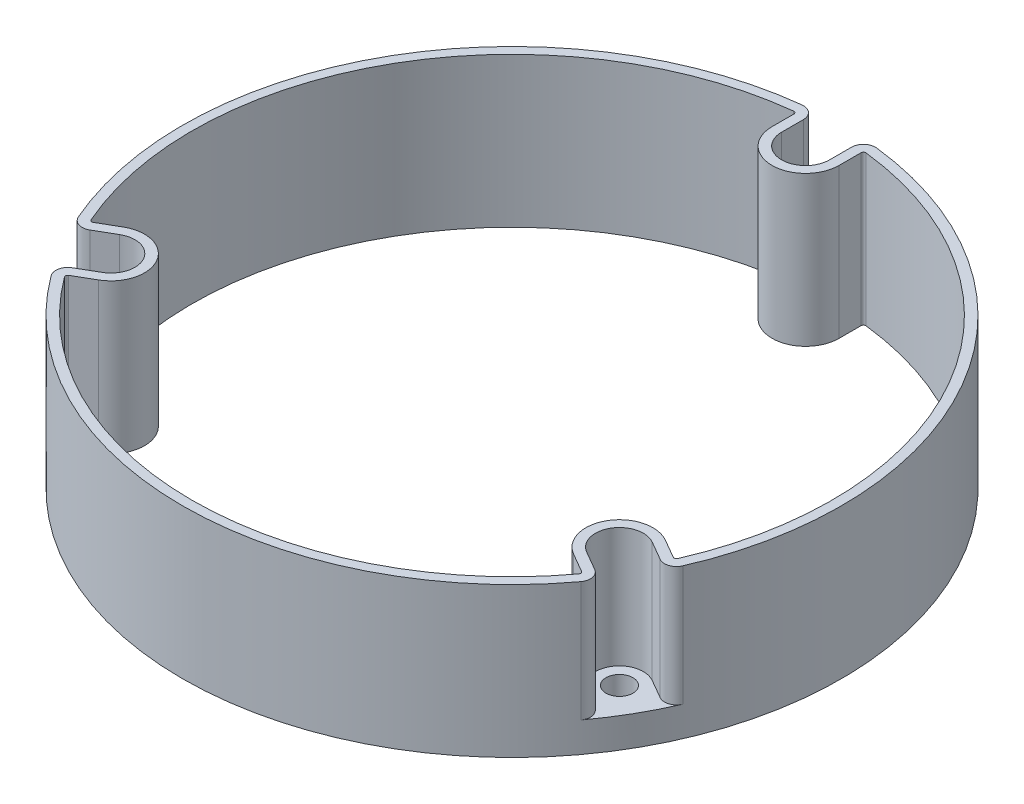
SolidWorks part; units mm, degrees
ref_plane "Front Plane" through (0, 0, 0) normal (0, 0, 1) x (1, 0, 0)
ref_plane "Top Plane" through (0, 0, 0) normal (0, 1, 0) x (1, 0, 0)
ref_plane "Right Plane" through (0, 0, 0) normal (1, 0, 0) x (0, 0, -1)
sketch "Sketch2" plane through (0, 0, 0) normal (0, 1, 0) x (1, 0, 0)
  line L0 (-4, 52.6593) -> (-4, 49)
  line L1 (-4, 49) -> (4, 49) construction
  line L2 (4, 49) -> (4, 52.6593)
  line L3 (0, 49) -> (0, 55) construction
  line L4 (47.6043, -22.8655) -> (44.4352, -21.0359)
  line L5 (40.4352, -27.9641) -> (43.6043, -29.7937)
  line L6 (-43.6043, -29.7937) -> (-40.4352, -27.9641)
  line L7 (-44.4352, -21.0359) -> (-47.6043, -22.8655)
  line L8 (0, 0) -> (0, 49) construction
  line L9 (0, 0) -> (42.4352, -24.5) construction
  arc A0 (-6.2264, 54.6464) -> (-50.4384, -21.931) centre (0, 0) ccw
  arc A1 (-4, 49) -> (4, 49) centre (0, 49) ccw
  arc A2 (-4, 54.8544) -> (4, 54.8544) centre (0, 0) cw construction
  arc A3 (44.4352, -21.0359) -> (40.4352, -27.9641) centre (42.4352, -24.5) ccw
  arc A4 (-40.4352, -27.9641) -> (-44.4352, -21.0359) centre (-42.4352, -24.5) ccw
  arc A5 (50.4384, -21.931) -> (6.2264, 54.6464) centre (0, 0) ccw
  arc A6 (-44.212, -32.7154) -> (44.212, -32.7154) centre (0, 0) ccw
  arc A7 (-44.212, -32.7154) -> (-43.6043, -29.7937) centre (-42.6043, -31.5258) cw
  arc A8 (-47.6043, -22.8655) -> (-50.4384, -21.931) centre (-48.6043, -21.1335) cw
  arc A9 (50.4384, -21.931) -> (47.6043, -22.8655) centre (48.6043, -21.1335) cw
  arc A10 (44.212, -32.7154) -> (43.6043, -29.7937) centre (42.6043, -31.5258) ccw
  arc A11 (6.2264, 54.6464) -> (4, 52.6593) centre (6, 52.6593) ccw
  arc A12 (-4, 52.6593) -> (-6.2264, 54.6464) centre (-6, 52.6593) ccw
  dimension "D1" = 110
  dimension "D2" = 4
  dimension "D6" = 2
  dimension "D3" = 6
  dimension "D5" = 120
  dimension "D4" = 3
extrude "Extrude-Thin1" add sketch "Sketch2" along normal blind 25 thin
sketch "Sketch3" plane through (0, 0, 0) normal (0, -1, 0) x (1, 0, 0)
  line L6 (-43.6043, 29.7937) -> (-40.4352, 27.9641)
  line L7 (-44.4352, 21.0359) -> (-47.6043, 22.8655)
  line L8 (-4, -52.6593) -> (-4, -49)
  line L9 (4, -49) -> (4, -52.6593)
  line L10 (47.6043, 22.8655) -> (44.4352, 21.0359)
  line L11 (40.4352, 27.9641) -> (43.6043, 29.7937)
  line L12 (-43.6043, 29.7937) -> (-40.4352, 27.9641)
  line L13 (-44.4352, 21.0359) -> (-47.6043, 22.8655)
  line L14 (-4, -52.6593) -> (-4, -49)
  line L15 (4, -49) -> (4, -52.6593)
  line L16 (47.6043, 22.8655) -> (44.4352, 21.0359)
  line L17 (40.4352, 27.9641) -> (43.6043, 29.7937)
  arc A0 (-44.212, 32.7154) -> (-50.4384, 21.931) centre (0, 0) ccw
  arc A1 (50.4384, 21.931) -> (44.212, 32.7154) centre (0, 0) ccw
  arc A2 (-6.2264, -54.6464) -> (6.2264, -54.6464) centre (0, 0) ccw
  circle A3 centre (-42.4352, 24.5) radius 2.25
  circle A4 centre (42.4352, 24.5) radius 2.25
  circle A5 centre (0, -49) radius 2.25
  arc A12 (-44.212, 32.7154) -> (-43.6043, 29.7937) centre (-42.6043, 31.5258) ccw
  arc A13 (-44.4352, 21.0359) -> (-40.4352, 27.9641) centre (-42.4352, 24.5) ccw
  arc A14 (-47.6043, 22.8655) -> (-50.4384, 21.931) centre (-48.6043, 21.1335) ccw
  arc A15 (-50.4384, 21.931) -> (-6.2264, -54.6464) centre (0, 0) ccw
  arc A16 (-6.2264, -54.6464) -> (-4, -52.6593) centre (-6, -52.6593) ccw
  arc A17 (4, -49) -> (-4, -49) centre (0, -49) ccw
  arc A18 (4, -52.6593) -> (6.2264, -54.6464) centre (6, -52.6593) ccw
  arc A19 (6.2264, -54.6464) -> (50.4384, 21.931) centre (0, 0) ccw
  arc A20 (50.4384, 21.931) -> (47.6043, 22.8655) centre (48.6043, 21.1335) ccw
  arc A21 (40.4352, 27.9641) -> (44.4352, 21.0359) centre (42.4352, 24.5) ccw
  arc A22 (43.6043, 29.7937) -> (44.212, 32.7154) centre (42.6043, 31.5258) ccw
  arc A23 (44.212, 32.7154) -> (-44.212, 32.7154) centre (0, 0) ccw
  arc A24 (-44.212, 32.7154) -> (-43.6043, 29.7937) centre (-42.6043, 31.5258) ccw
  arc A25 (-44.4352, 21.0359) -> (-40.4352, 27.9641) centre (-42.4352, 24.5) ccw
  arc A26 (-47.6043, 22.8655) -> (-50.4384, 21.931) centre (-48.6043, 21.1335) ccw
  arc A28 (-6.2264, -54.6464) -> (-4, -52.6593) centre (-6, -52.6593) ccw
  arc A29 (4, -49) -> (-4, -49) centre (0, -49) ccw
  arc A30 (4, -52.6593) -> (6.2264, -54.6464) centre (6, -52.6593) ccw
  arc A32 (50.4384, 21.931) -> (47.6043, 22.8655) centre (48.6043, 21.1335) ccw
  arc A33 (40.4352, 27.9641) -> (44.4352, 21.0359) centre (42.4352, 24.5) ccw
  arc A34 (43.6043, 29.7937) -> (44.212, 32.7154) centre (42.6043, 31.5258) ccw
  dimension "D2" = 4.5
  dimension "D1" = 0
extrude "Boss-Extrude1" add sketch "Sketch3" against normal blind 5
